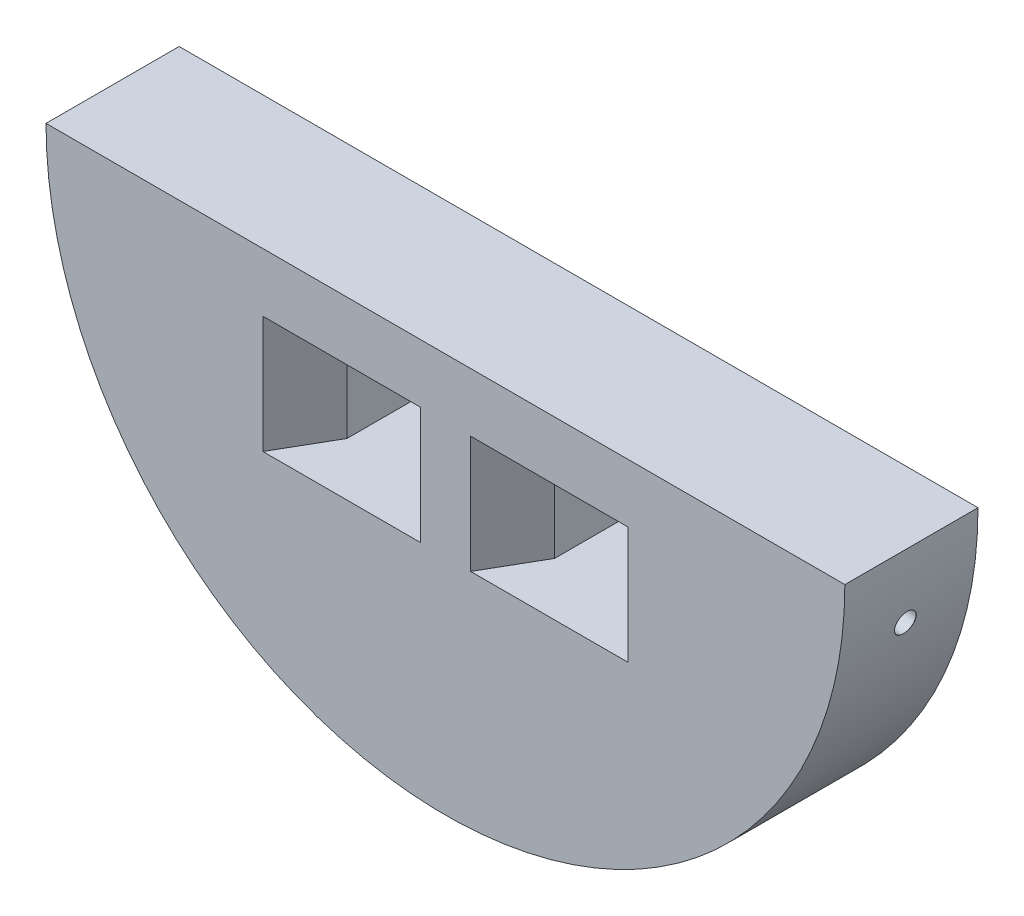
SolidWorks part; units mm, degrees
ref_plane "Front Plane" through (0, 0, 0) normal (0, 0, 1) x (1, 0, 0)
ref_plane "Top Plane" through (0, 0, 0) normal (0, 1, 0) x (1, 0, 0)
ref_plane "Right Plane" through (0, 0, 0) normal (1, 0, 0) x (0, 0, -1)
sketch "Sketch1" plane through (0, 0, 0) normal (0, 0, 1) x (1, 0, 0)
  line L0 (-150, 0) -> (0, 0)
  line L3 (-64.5, -33) -> (-46.5, -33)
  line L4 (-64.5, -33) -> (-64.5, -15)
  line L5 (-64.5, -15) -> (-46.5, -15)
  line L6 (-46.5, -33) -> (-46.5, -15)
  line L7 (-103.5, -33) -> (-85.5, -33)
  line L8 (-103.5, -33) -> (-103.5, -15)
  line L9 (-103.5, -15) -> (-85.5, -15)
  line L10 (-85.5, -33) -> (-85.5, -15)
  arc A1 (-150, 0) -> (0, 0) centre (-75, 0) ccw
  point P0 (-94.5, -15)
  point P13 (-55.5, -15)
  dimension "D1" = 19.5
  dimension "D7" = 75
  dimension "D2" = 15
  dimension "D3" = 19.5
  dimension "D4" = 18
extrude "Boss-Extrude1" add sketch "Sketch1" along normal blind 25
hole_wizard "Ø4.0mm Dowel Hole2" positions "3DSketch2" profile "Sketch4" hole size "Ø4.0" standard "ANSI Metric"
sketch3d "3DSketch2"
  line L2 (0, 0, 25) -> (0, 0, 0) construction
  line L4 (0, 0, 25) -> (0, 0, 0) construction
  line L5 (0, 0, 12.5) -> (-1.1394, -13.0236, 12.5) construction
  line L8 (-75, 0, 0) -> (-75, 0, 25) construction
  line L9 (0, 0, 0) -> (-150, 0, 0) construction
  line L10 (0, 0, 25) -> (-150, 0, 25) construction
  line L12 (-75, 0, 12.5) -> (-1.1394, -13.0236, 12.5) construction
  line L16 (-75, 0, 12.5) -> (0, 0, 12.5) construction
  point P0 (-1.1394, -13.0236, 12.5)
  point P16 (-1.1394, -13.0236, 12.5)
  point P23 (-1.1394, -13.0236, 12.5)
  point P25 (-1.1394, -13.0236, 12.5)
  dimension "D1" = 10
sketch "Sketch4" plane through (-1.1394, -13.0236, 12.5) normal (0, 0, 1) x (0.1736, 0.9848, 0)
  line L0 (0, 0) -> (0, 17.2017)
  line L1 (0, 17.2017) -> (2, 16)
  line L2 (2, 16) -> (2, 0.025)
  line L3 (2, 0.025) -> (2.025, 0)
  line L5 (2.025, 0) -> (0, 0)
  line L6 (-2, 0.025) -> (-2.025, 0) construction
  line L10 (0, 17.2017) -> (-2, 16) construction
  line L11 (0, -6.35) -> (0, 107.95) construction
  dimension "Hole Dia." = 4
  dimension "Hole Depth" = 16
  dimension "Near C'Sink Dia." = 4.05
  dimension "Near C'Sink Angle" = 90
  dimension "Drill Angle" = 118
pattern_circular "CirPattern1" count 5 over 160 about axis through (-75, 0, 0) along (0, 0, 1) of "Ø4.0mm Dowel Hole2"
chamfer "Chamfer1" distance 15 angle 30 2 edges at (-94.5, -15, 0) (-55.5, -15, 0)
chamfer "Chamfer3" distance 10 angle 30 4 edges at (-103.5, -24, 25) (-85.5, -24, 25) (-46.5, -24, 25) (-64.5, -24, 25)
chamfer "Chamfer4" distance 4 angle 60 2 edges at (-55.5, -15, 25) (-94.5, -15, 25)
